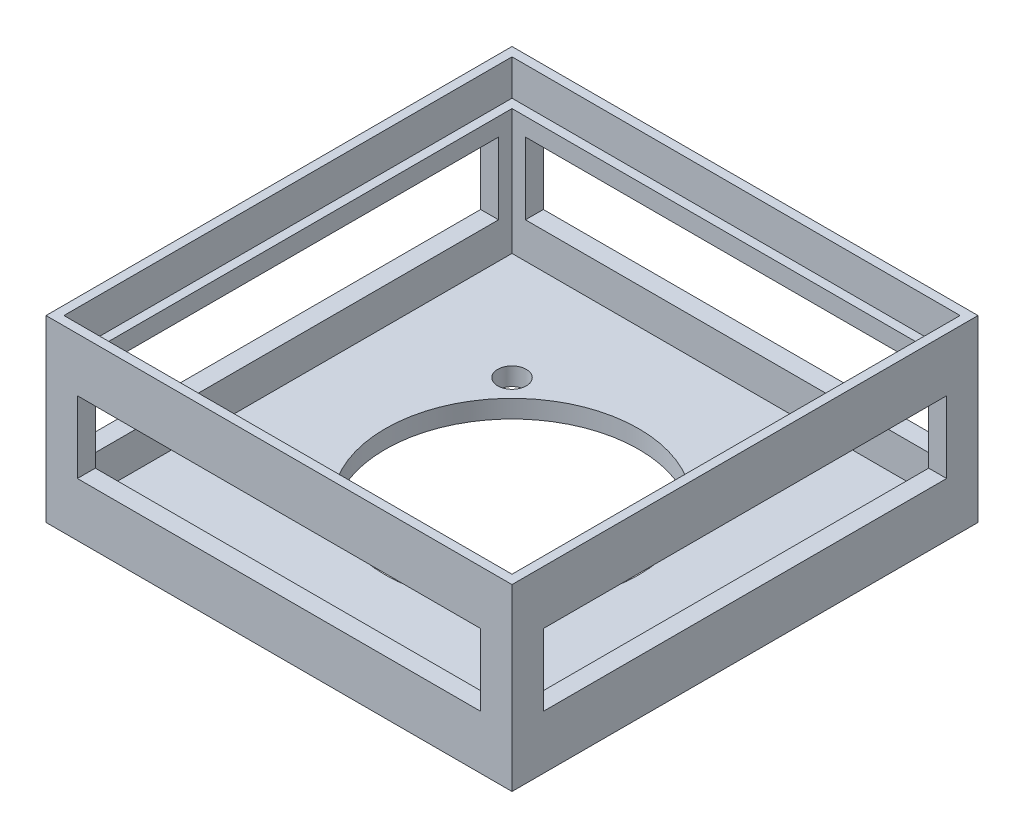
SolidWorks part; units mm, degrees
ref_plane "前视基准面" through (0, 0, 0) normal (0, 0, 1) x (1, 0, 0)
ref_plane "上视基准面" through (0, 0, 0) normal (0, 1, 0) x (1, 0, 0)
ref_plane "右视基准面" through (0, 0, 0) normal (1, 0, 0) x (0, 0, -1)
other "Configuration Table"
sketch "草图1" plane through (0, 0, 0) normal (0, 1, 0) x (1, 0, 0)
  line L0 (0, 15) -> (0, -15) construction
  line L1 (-15, -15) -> (15, -15)
  line L2 (-15, -15) -> (-15, 15)
  line L3 (-15, 15) -> (15, 15)
  line L4 (15, -15) -> (15, 15)
  line L5 (-15, -15) -> (15, 15) construction
  line L6 (-15, 15) -> (15, -15) construction
  line L7 (-15, 15) -> (-12, 15)
  line L8 (-15, 15) -> (-15, 12)
  line L9 (-15, 12) -> (-12, 12)
  line L10 (-12, 15) -> (-12, 12)
  line L11 (-15, 0) -> (15, 0) construction
  line L12 (-25, 25) -> (25, 25)
  line L13 (25, -25) -> (25, 25)
  line L14 (-25, -25) -> (25, -25)
  line L15 (-25, -25) -> (-25, 25)
  line L16 (-10, 10) -> (10, 10)
  line L17 (10, -10) -> (10, 10)
  line L18 (-10, -10) -> (10, -10)
  line L19 (-10, -10) -> (-10, 10)
  line L20 (-26, 26) -> (26, 26)
  line L21 (26, -26) -> (26, 26)
  line L22 (-26, -26) -> (26, -26)
  line L23 (-26, -26) -> (-26, 26)
  line L24 (-24, 24) -> (24, 24)
  line L25 (24, -24) -> (24, 24)
  line L26 (-24, -24) -> (24, -24)
  line L27 (-24, -24) -> (-24, 24)
  circle A0 centre (-12, 12) radius 1.6
  circle A1 centre (12, 12) radius 1.6
  circle A2 centre (12, -12) radius 1.6
  circle A3 centre (-12, -12) radius 1.6
  point P0 (0, 0)
  dimension "D4" = 3.2
  dimension "D1" = 30
  dimension "D2" = 30
  dimension "D3" = 3
  dimension "D5" = 10
  dimension "D7" = 1
  dimension "D6" = 5
  dimension "D8" = 1
extrude "凸台-拉伸5" add sketch "草图1" along normal blind 20 contours A3 | L19 L18 L17 L16 | A1 | L9 A0 L10 | L10 A0 L9 | L23 L20 L21 L22 | A2
shell "抽壳6" thickness 2
sketch "草图4" plane through (0, 20, 0) normal (0, 1, 0) x (1, 0, 0)
  line L1 (-25, 25) -> (-25, -25)
  line L2 (-26, 26) -> (26, 26)
  line L3 (-26, 26) -> (-26, -26)
  line L4 (-26, -26) -> (26, -26)
  line L5 (26, 26) -> (26, -26)
  line L6 (-25, -25) -> (25, -25)
  line L7 (25, 25) -> (25, -25)
  line L8 (-25, 25) -> (25, 25)
  line L9 (-24, 24) -> (24, 24)
  line L10 (24, 24) -> (24, -24)
  line L11 (-24, -24) -> (24, -24)
  line L12 (-24, 24) -> (-24, -24)
  line M2 (24, -24) -> (-24, -24)
  line M3 (-24, -24) -> (-24, 24)
  line M4 (-24, 24) -> (24, 24)
  line M5 (24, 24) -> (24, -24)
  dimension "D1" = 1
  dimension "D2" = 2
extrude "切除-拉伸4" cut sketch "草图4" against normal blind 4 contours L8 L1 L6 L7 M5 M2 M3 M4
sketch "草图5" plane through (0, 0, -24) normal (0, 0, 1) x (1, 0, 0)
  line L0 (-0.0001, 20) -> (0.0001, 20) construction
  line L1 (-26, 20) -> (26, 20) construction
  line L2 (-26, 10) -> (26, 10) construction
  line L3 (-26, 20) -> (-26, 0) construction
  line L4 (26, 20) -> (26, 0) construction
  line L5 (-0.0001, 20) -> (0, 0) construction
  line L7 (22.5, 14) -> (-22.5, 14)
  line L8 (22.5, 14) -> (22.5, 6)
  line L9 (22.5, 6) -> (-22.5, 6)
  line L10 (-22.5, 14) -> (-22.5, 6)
  line L11 (22.5, 14) -> (-22.5, 6) construction
  line L12 (22.5, 6) -> (-22.5, 14) construction
  point P5 (0, 20)
  point P11 (0, 10)
  dimension "D1" = 45
  dimension "D2" = 8
extrude "切除-拉伸5" cut sketch "草图5" against normal through all both and the other way through all
sketch "草图6" plane through (-24, 0, 0) normal (1, 0, 0) x (0, 0, -1)
  line L0 (0, 20) -> (0, 0) construction
  line L1 (-26, 20) -> (26, 20) construction
  line L2 (-26, 10) -> (26, 10) construction
  line L3 (-26, 20) -> (-26, 0) construction
  line L4 (26, 20) -> (26, 0) construction
  line L6 (22.5, 6) -> (-22.5, 6)
  line L7 (22.5, 6) -> (22.5, 14)
  line L8 (22.5, 14) -> (-22.5, 14)
  line L9 (-22.5, 6) -> (-22.5, 14)
  line L10 (22.5, 6) -> (-22.5, 14) construction
  line L11 (22.5, 14) -> (-22.5, 6) construction
  point P11 (0, 10)
  dimension "D1" = 45
  dimension "D2" = 8
extrude "切除-拉伸6" cut sketch "草图6" against normal through all both and the other way through all
sketch "草图7" plane through (0, 0, 0) normal (0, -1, 0) x (1, 0, 0)
  circle A0 centre (0, 0) radius 14.1421
  dimension "D1" = 28.2843
extrude "切除-拉伸7" cut sketch "草图7" against normal blind 10
